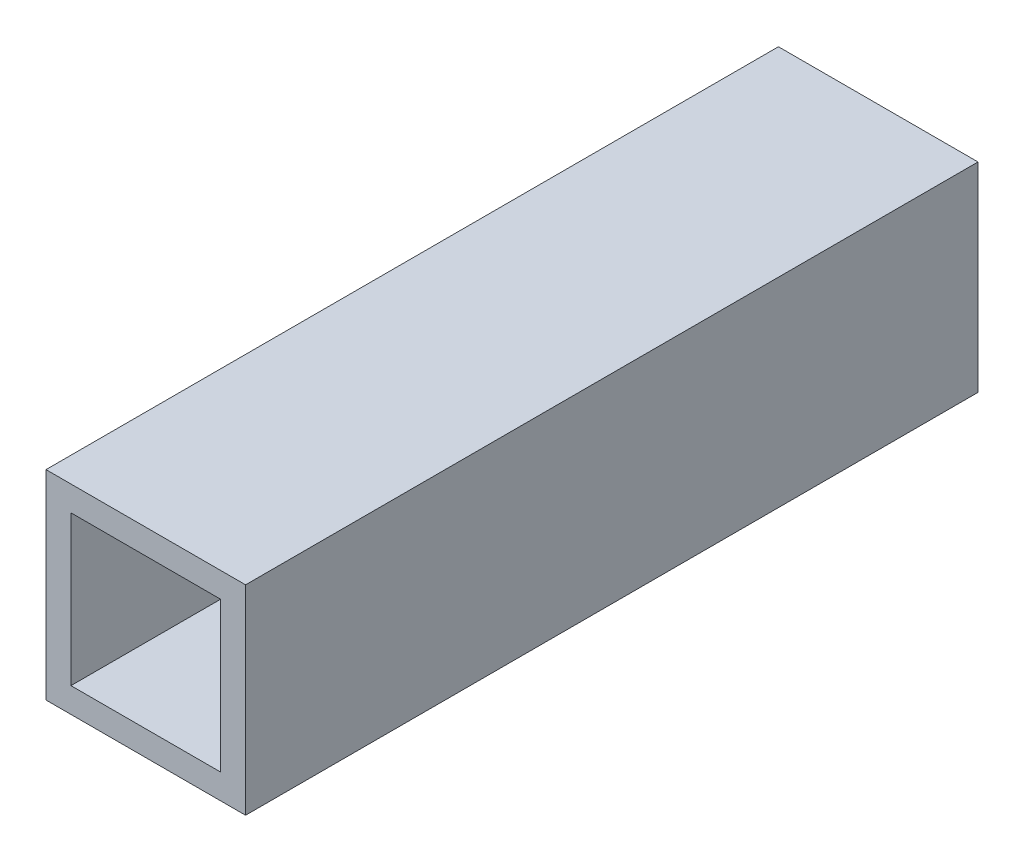
SolidWorks part; units mm, degrees
ref_plane "Front Plane" through (0, 0, 0) normal (0, 0, 1) x (1, 0, 0)
ref_plane "Top Plane" through (0, 0, 0) normal (0, 1, 0) x (1, 0, 0)
ref_plane "Right Plane" through (0, 0, 0) normal (1, 0, 0) x (0, 0, -1)
sketch "Sketch1" plane through (0, 0, 0) normal (0, 0, 1) x (1, 0, 0)
  line L0 (-9.525, -9.525) -> (9.525, -9.525)
  line L1 (-12.7, -12.7) -> (12.7, -12.7)
  line L2 (-12.7, -12.7) -> (-12.7, 12.7)
  line L3 (-12.7, 12.7) -> (12.7, 12.7)
  line L4 (12.7, -12.7) -> (12.7, 12.7)
  line L5 (9.525, -9.525) -> (9.525, 9.525)
  line L6 (-9.525, 9.525) -> (9.525, 9.525)
  line L7 (-9.525, -9.525) -> (-9.525, 9.525)
  dimension "D1" = 25.4
  dimension "D2" = 3.175
extrude "Boss-Extrude1" add sketch "Sketch1" along normal blind 93.218
